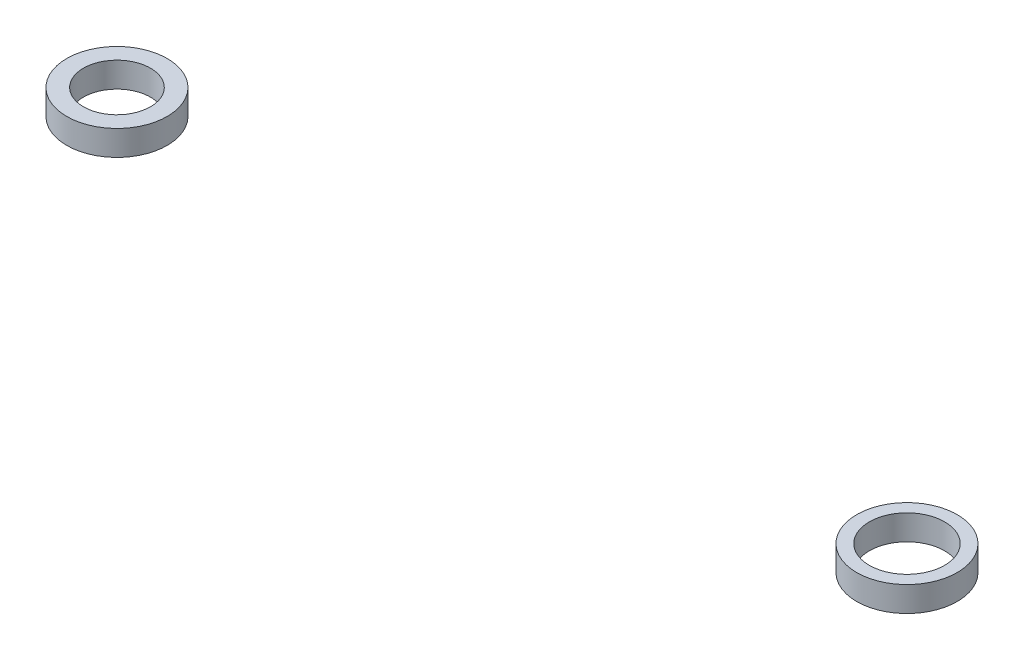
SolidWorks part; units mm, degrees
ref_plane "Front Plane" through (0, 0, 0) normal (0, 0, 1) x (1, 0, 0)
ref_plane "Top Plane" through (0, 0, 0) normal (0, 1, 0) x (1, 0, 0)
ref_plane "Right Plane" through (0, 0, 0) normal (1, 0, 0) x (0, 0, -1)
sketch "Sketch1" plane through (0, 0, 0) normal (0, 1, 0) x (1, 0, 0)
  circle A0 centre (0, 0) radius 4
  circle A1 centre (94.37, 0) radius 4.5
  circle A2 centre (0, 0) radius 6
  circle A3 centre (94.37, 0) radius 6
  dimension "D1" = 8
  dimension "D2" = 9
  dimension "D3" = 12
extrude "Boss-Extrude1" add sketch "Sketch1" along normal blind 3
